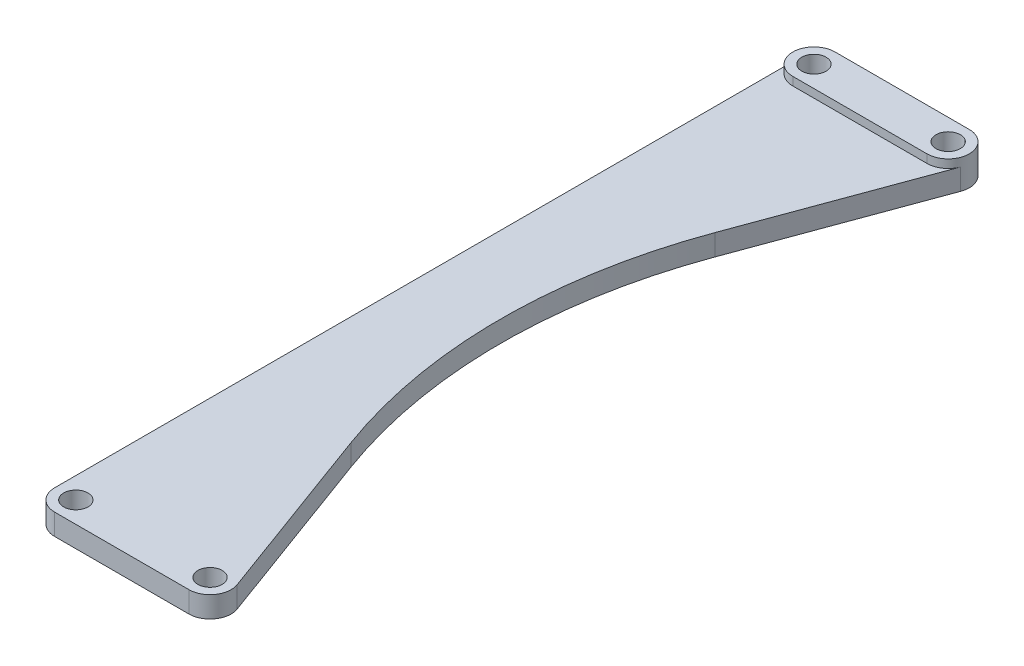
SolidWorks part; units mm, degrees
ref_plane "Front Plane" through (0, 0, 0) normal (0, 0, 1) x (1, 0, 0)
ref_plane "Top Plane" through (0, 0, 0) normal (0, 1, 0) x (1, 0, 0)
ref_plane "Right Plane" through (0, 0, 0) normal (1, 0, 0) x (0, 0, -1)
sketch "Sketch1" plane through (0, 0, 0) normal (0, 1, 0) x (1, 0, 0)
  line L0 (0, 0) -> (25.4, 0) construction
  line L1 (0, 0) -> (0, -139.7) construction
  line L2 (-4, -69.85) -> (4, -69.85) construction
  line L3 (-4, -143.7) -> (-4, 4)
  line L4 (-4, 4) -> (25.4, 4)
  line L5 (-4, -143.7) -> (25.4, -143.7)
  line L6 (4, -69.85) -> (29.1546, -1.3794)
  line L7 (4, -69.85) -> (29.1546, -138.3206)
  circle A0 centre (0, 0) radius 2.3
  circle A1 centre (25.4, 0) radius 2.3
  circle A2 centre (25.4, -139.7) radius 2.3
  circle A3 centre (0, -139.7) radius 2.3
  arc A4 (25.4, -143.7) -> (29.1546, -138.3206) centre (25.4, -139.7) ccw
  arc A5 (29.1546, -1.3794) -> (25.4, 4) centre (25.4, 0) ccw
  point P15 (0, -69.85)
  point P18 (-4, -69.85)
  dimension "D1" = 4.6
  dimension "D8" = 4
  dimension "D4" = 25.4
  dimension "D5" = 139.7
  dimension "D6" = 8
  dimension "D7" = 4
  dimension "D2" = 2
  dimension "D3" = 2
extrude "Boss-Extrude2" add sketch "Sketch1" along normal blind 4
fillet "Fillet1" radius 4 2 edges at (-4, 2, -4) (-4, 2, 143.7)
fillet "Fillet2" radius 100 1 edges at (4, 2, 69.85)
sketch "Sketch2" plane through (0, 4, 0) normal (0, 1, 0) x (1, 0, 0)
  line L0 (0, -4) -> (25.4, -4)
  line L1 (0, 4) -> (25.4, 4)
  arc A0 (0, 4) -> (0, -4) centre (0, 0) ccw
  arc A1 (25.4, -4) -> (25.4, 4) centre (25.4, 0) ccw
  circle A4 centre (0, 0) radius 2.3 construction
  circle A5 centre (25.4, 0) radius 2.3 construction
  circle A6 centre (0, 0) radius 2.3
  circle A7 centre (25.4, 0) radius 2.3
extrude "Boss-Extrude3" add sketch "Sketch2" along normal blind 1.5753
